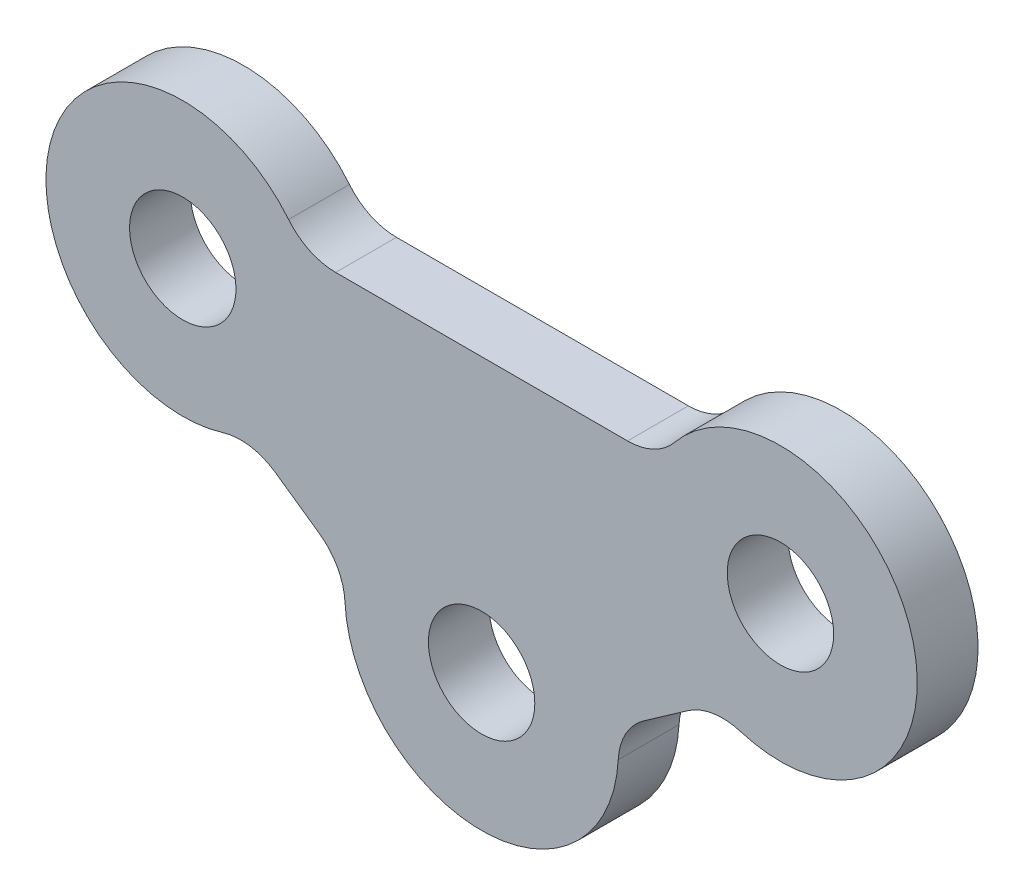
SolidWorks part; units mm, degrees
ref_plane "Front Plane" through (0, 0, 0) normal (0, 0, 1) x (1, 0, 0)
ref_plane "Top Plane" through (0, 0, 0) normal (0, 1, 0) x (1, 0, 0)
ref_plane "Right Plane" through (0, 0, 0) normal (1, 0, 0) x (0, 0, -1)
sketch "Sketch1" plane through (0, 0, 0) normal (0, 0, 1) x (1, 0, 0)
  line L0 (9.8298, 6.8829) -> (0, 0) construction
  line L1 (0, 0) -> (-7.6504, 0) construction
  line L2 (0, 0) -> (0, 11.4384) construction
  line L3 (0, 0) -> (0, -5.0479) construction
  line L4 (6.7801, 2.3059) -> (5.3441, 1.3004)
  line L5 (4.8, 9) -> (-4.8, 9)
  line L7 (-6.7801, 2.3059) -> (-5.3441, 1.3004)
  circle A0 centre (0, 0) radius 1.75
  arc A1 (-4.4939, -0.2339) -> (4.4939, -0.2339) centre (0, 0) ccw
  circle A2 centre (9.8298, 6.8829) radius 1.75
  arc A3 (-6.7801, 2.3059) -> (-8.5126, 2.58) centre (-7.9272, 0.6676) ccw
  arc A4 (8.5126, 2.58) -> (6.3476, 9.7332) centre (9.8298, 6.8829) ccw
  arc A5 (-5.3441, 1.3004) -> (-4.4939, -0.2339) centre (-6.4912, -0.3379) cw
  arc A6 (-6.3476, 9.7332) -> (-4.8, 9) centre (-4.8, 11) ccw
  arc A7 (4.8, 9) -> (6.3476, 9.7332) centre (4.8, 11) ccw
  arc A8 (6.7801, 2.3059) -> (8.5126, 2.58) centre (7.9272, 0.6676) cw
  circle A9 centre (-9.8298, 6.8829) radius 1.75
  arc A10 (-8.5126, 2.58) -> (-6.3476, 9.7332) centre (-9.8298, 6.8829) cw
  arc A11 (5.3441, 1.3004) -> (4.4939, -0.2339) centre (6.4912, -0.3379) ccw
  point P7 (-7.6749, 2.9325)
  point P17 (-4.4493, 0.6739)
  point P22 (-5.8589, 9)
  point P26 (5.8589, 9)
  point P30 (7.6749, 2.9325)
  point P31 (0, 9)
  point P34 (4.4493, 0.6739)
  dimension "D1" = 3.5
  dimension "D2" = 9
  dimension "D3" = 3.5
  dimension "D4" = 9
  dimension "D10" = 4.5
  dimension "D8" = 2
  dimension "D5" = 35
  dimension "D6" = 12
  dimension "D7" = 2
extrude "Boss-Extrude1" add sketch "Sketch1" along normal blind 2
